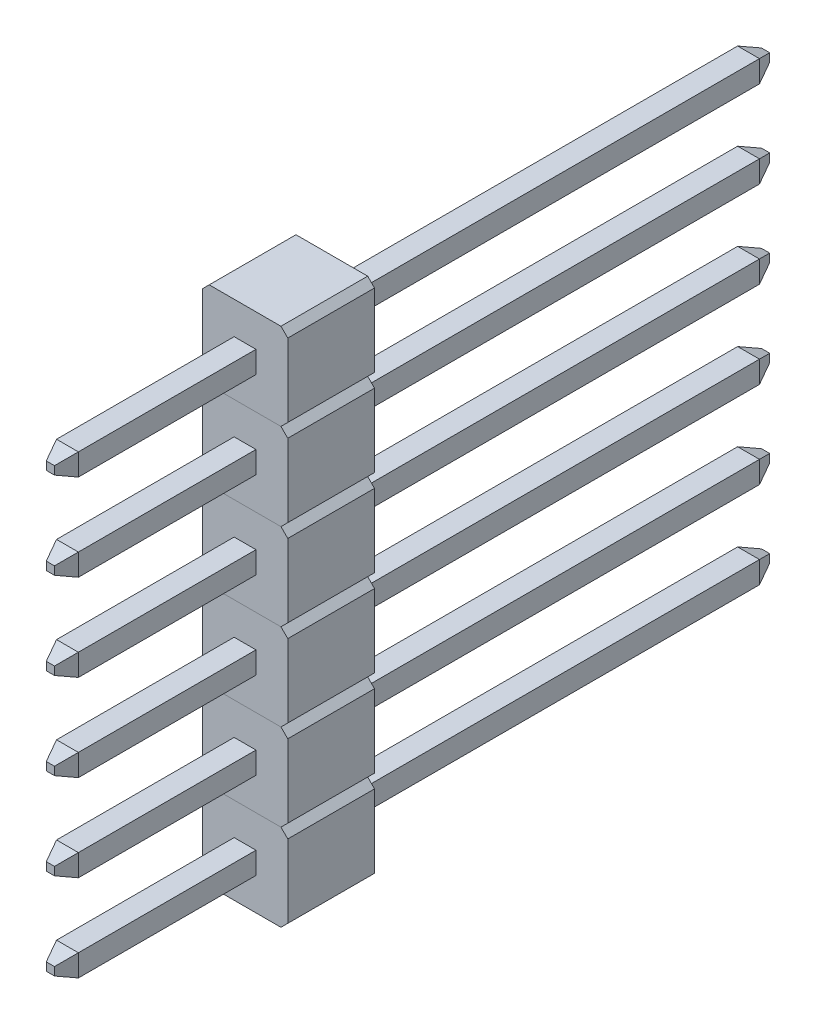
SolidWorks part; units mm, degrees
ref_plane "Plan de face" through (0, 0, 0) normal (0, 0, 1) x (1, 0, 0)
ref_plane "Plan de dessus" through (0, 0, 0) normal (0, 1, 0) x (1, 0, 0)
ref_plane "Plan de droite" through (0, 0, 0) normal (1, 0, 0) x (0, 0, -1)
sketch "Esquisse1" plane through (0, 0, 0) normal (0, 0, 1) x (1, 0, 0)
  line L1 (-1.25, 1.27) -> (1.25, 1.27)
  line L2 (-1.25, 1.27) -> (-1.25, -1.27)
  line L3 (-1.25, -1.27) -> (1.25, -1.27)
  line L4 (1.25, 1.27) -> (1.25, -1.27)
  line L5 (-1.25, 1.27) -> (1.25, -1.27) construction
  line L6 (-1.25, -1.27) -> (1.25, 1.27) construction
  point P0 (0, 0)
  dimension "D1" = 2.5
  dimension "D2" = 2.54
extrude "Base" add sketch "Esquisse1" along normal blind 2.54
sketch "Esquisse3" plane through (0, 0, 2.54) normal (0, 0, 1) x (1, 0, 0)
  line L1 (-0.32, -0.32) -> (0.32, -0.32)
  line L2 (-0.32, -0.32) -> (-0.32, 0.32)
  line L3 (-0.32, 0.32) -> (0.32, 0.32)
  line L4 (0.32, -0.32) -> (0.32, 0.32)
  line L5 (-0.32, -0.32) -> (0.32, 0.32) construction
  line L6 (-0.32, 0.32) -> (0.32, -0.32) construction
  point P0 (0, 0)
  dimension "D1" = 0.64
extrude "A" add sketch "Esquisse3" along normal blind 5.7
sketch "Esquisse4" plane through (0, 0, 0) normal (0, 0, -1) x (-1, 0, 0)
  line L1 (-0.32, 0.32) -> (0.32, 0.32)
  line L2 (-0.32, 0.32) -> (-0.32, -0.32)
  line L3 (-0.32, -0.32) -> (0.32, -0.32)
  line L4 (0.32, 0.32) -> (0.32, -0.32)
  line L5 (-0.32, 0.32) -> (0.32, -0.32) construction
  line L6 (-0.32, -0.32) -> (0.32, 0.32) construction
  point P0 (0, 0)
  dimension "D1" = 0.64
extrude "B" add sketch "Esquisse4" along normal blind 12.7
chamfer "Chanfrein2" distance 0.2 angle 45 4 edges at (1.25, -1.27, 1.27) (1.25, 1.27, 1.27) (-1.25, 1.27, 1.27) (-1.25, -1.27, 1.27)
chamfer "Chanfrein3" distance 0.5 distance2 0.2 8 edges at (0, -0.32, 8.24) (-0.32, 0, 8.24) (0, 0.32, 8.24) (0.32, 0, 8.24) (0, -0.32, -12.7) (0.32, 0, -12.7) (0, 0.32, -12.7) (-0.32, 0, -12.7)
pattern_linear "Répétition linéaire2" count 6 spacing 2.54 along (0, 1, 0) of bodies 103
